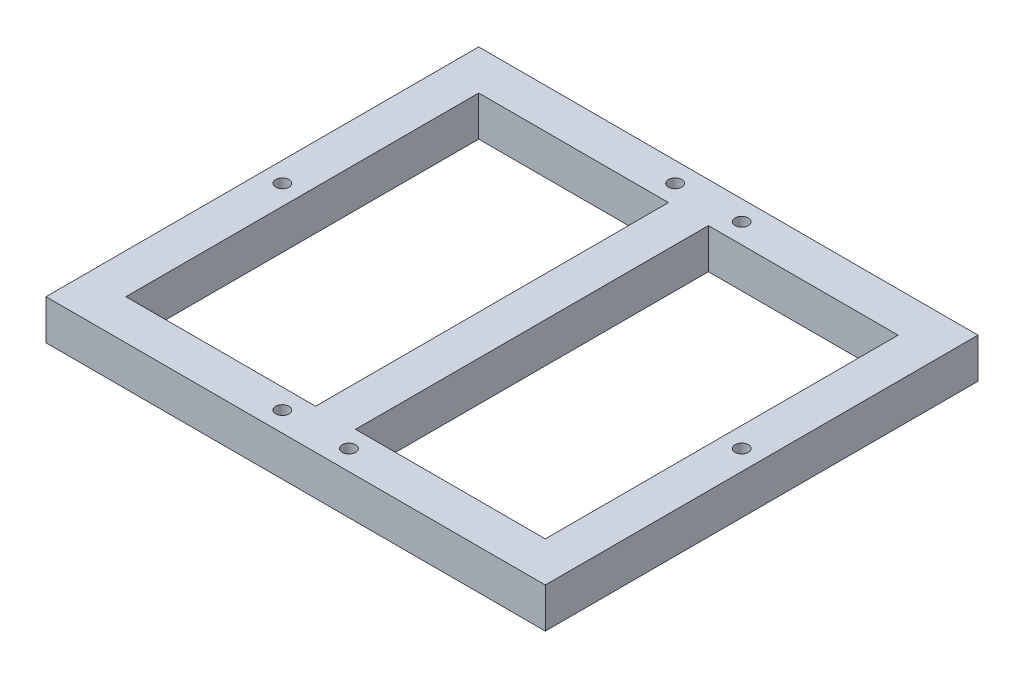
SolidWorks part; units mm, degrees
material "1060 Alloy"
ref_plane "Front Plane" through (0, 0, 0) normal (0, 0, 1) x (1, 0, 0)
ref_plane "Top Plane" through (0, 0, 0) normal (0, 1, 0) x (1, 0, 0)
ref_plane "Right Plane" through (0, 0, 0) normal (1, 0, 0) x (0, 0, -1)
sketch "Sketch1" plane through (0, 0, 0) normal (0, 1, 0) x (1, 0, 0)
  line L0 (-63, -53) -> (-63, 53)
  line L5 (-75, -65) -> (75, -65)
  line L6 (-75, -65) -> (-75, 65)
  line L11 (-75, 65) -> (75, 65)
  line L12 (75, -65) -> (75, 65)
  line L13 (-75, -65) -> (75, 65) construction
  line L14 (-75, 65) -> (75, -65) construction
  line L15 (-63, 53) -> (-6, 53)
  line L16 (63, -53) -> (63, 53)
  line L17 (-63, -53) -> (-6, -53)
  line L18 (-6, 53) -> (-6, -53)
  line L19 (0, 58.6664) -> (0, 53) construction
  line L20 (6, 53) -> (6, -53)
  line L21 (6, 53) -> (63, 53)
  line L22 (-63, 53) -> (63, 53) construction
  line L23 (0, 0) -> (0, -60.108) construction
  line L24 (6, -53) -> (63, -53)
  line L25 (-63, -53) -> (63, -53) construction
  point P0 (0, 0)
  dimension "D1" = 130
  dimension "D2" = 150
  dimension "D3" = 12
  dimension "D4" = 6
extrude "Boss-Extrude1" add sketch "Sketch1" along normal mid plane 12
sketch "Sketch2" plane through (0, 6, 0) normal (0, 1, 0) x (1, 0, 0)
  line L0 (0, 77.1059) -> (0, -82.5433) construction
  line L1 (-93.9237, 0) -> (98.4083, 0) construction
  line L2 (-63, 53) -> (-63, -53) construction
  line L3 (-30.5326, -59) -> (32.8123, -59) construction
  line L4 (-63, -53) -> (-6, -53) construction
  circle A0 centre (-69, 0) radius 2
  circle A1 centre (69, 0) radius 2
  circle A2 centre (-10, -59) radius 2
  circle A3 centre (10, -59) radius 2
  circle A4 centre (-10, 59) radius 2
  circle A5 centre (10, 59) radius 2
  dimension "D2" = 4
  dimension "D4" = 10
  dimension "D5" = 4
  dimension "D1" = 6
  dimension "D3" = 6
extrude "Cut-Extrude1" cut sketch "Sketch2" against normal through all
